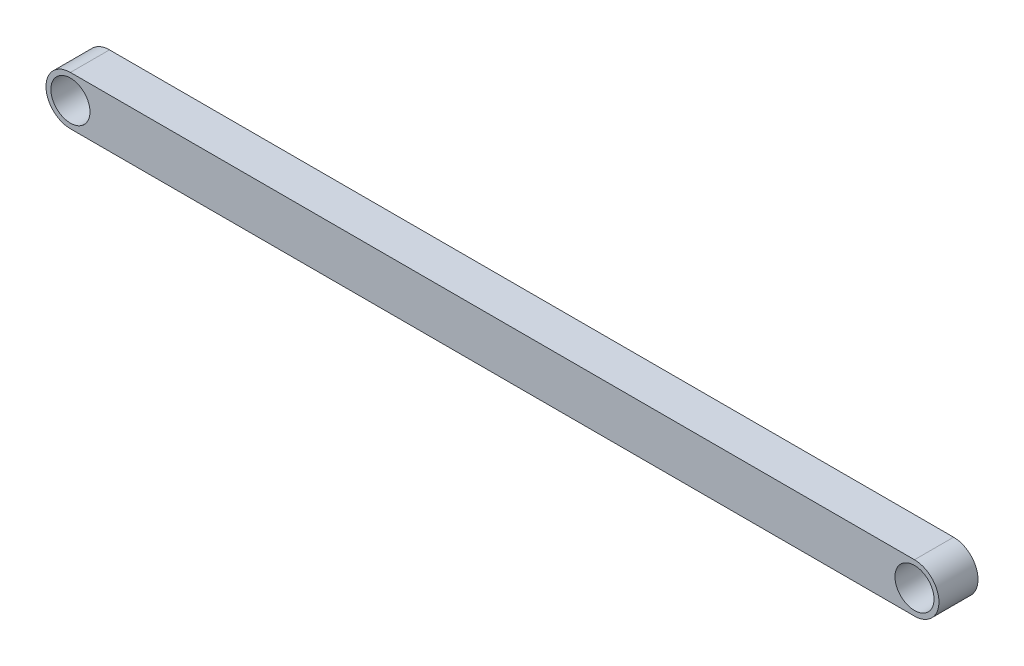
SolidWorks part; units mm, degrees
ref_plane "Front Plane" through (0, 0, 0) normal (0, 0, 1) x (1, 0, 0)
ref_plane "Top Plane" through (0, 0, 0) normal (0, 1, 0) x (1, 0, 0)
ref_plane "Right Plane" through (0, 0, 0) normal (1, 0, 0) x (0, 0, -1)
sketch "Sketch1" plane through (0, 0, 0) normal (0, 0, 1) x (1, 0, 0)
  line L0 (0, 0) -> (43.2, 0) construction
  line L1 (0, 1.25) -> (43.2, 1.25)
  line L2 (0, -1.25) -> (43.2, -1.25)
  arc A0 (0, 1.25) -> (0, -1.25) centre (0, 0) ccw
  arc A1 (43.2, -1.25) -> (43.2, 1.25) centre (43.2, 0) ccw
  circle A2 centre (0, 0) radius 1
  circle A3 centre (43.2, 0) radius 1
  point P3 (21.6, 0)
  dimension "D1" = 2
  dimension "D2" = 2
  dimension "D3" = 43.2
  dimension "D4" = 2.5
extrude "Boss-Extrude1" add sketch "Sketch1" along normal blind 2
